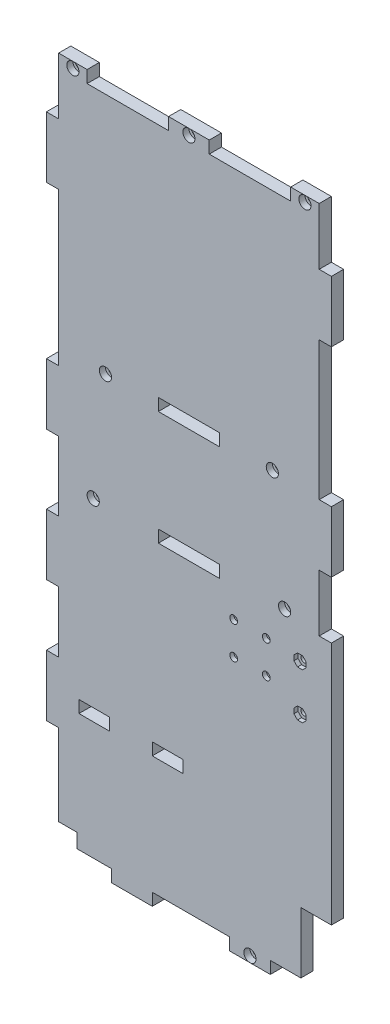
SolidWorks part; units mm, degrees
ref_plane "Plan de face" through (0, 0, 0) normal (0, 0, 1) x (1, 0, 0)
ref_plane "Plan de dessus" through (0, 0, 0) normal (0, 1, 0) x (1, 0, 0)
ref_plane "Plan de droite" through (0, 0, 0) normal (1, 0, 0) x (0, 0, -1)
sketch "Esquisse1" plane through (0, 0, 0) normal (0, 0, 1) x (1, 0, 0)
  line L0 (-67.6282, -207.2903) -> (-41.6282, -207.2903)
  line L1 (-67.6282, 126.7097) -> (-53.6282, 126.7097)
  line L2 (-67.6282, 126.7097) -> (-67.6282, 98.7097)
  line L3 (16.3718, -213.2903) -> (36.3718, -213.2903)
  line L4 (66.3718, 98.7097) -> (66.3718, 68.7097)
  line L5 (-67.6282, -100.2903) -> (-67.6282, -130.2903)
  line L6 (-67.6282, 98.7097) -> (-73.6282, 98.7097)
  line L7 (46.3718, 126.7097) -> (60.3718, 126.7097)
  line L8 (-67.6282, -70.2903) -> (-73.6282, -70.2903)
  line L9 (-67.6282, 68.7097) -> (-73.6282, 68.7097)
  line L10 (-73.6282, 98.7097) -> (-73.6282, 68.7097)
  line L11 (16.3718, -207.2903) -> (16.3718, -213.2903)
  line L12 (66.3718, -207.2903) -> (36.3718, -207.2903)
  line L13 (-67.6282, -6.2903) -> (-73.6282, -6.2903)
  line L14 (-67.6282, 68.7097) -> (-67.6282, -6.2903)
  line L15 (36.3718, -207.2903) -> (36.3718, -213.2903)
  line L16 (-67.6282, -36.2903) -> (-73.6282, -36.2903)
  line L17 (-73.6282, -6.2903) -> (-73.6282, -36.2903)
  line L18 (66.3718, 0.7097) -> (66.3718, -29.2903)
  line L19 (-53.6282, 126.7097) -> (-53.6282, 120.7097)
  line L20 (-53.6282, 120.7097) -> (-13.6282, 120.7097)
  line L21 (-13.6282, 120.7097) -> (-13.6282, 126.7097)
  line L22 (6.3718, 126.7097) -> (-13.6282, 126.7097)
  line L23 (66.3718, -57.2903) -> (66.3718, -207.2903)
  line L24 (66.3718, 68.7097) -> (60.3718, 68.7097)
  line L25 (6.3718, 126.7097) -> (6.3718, 120.7097)
  line L26 (66.3718, 0.7097) -> (60.3718, 0.7097)
  line L27 (66.3718, -57.2903) -> (60.3718, -57.2903)
  line L28 (6.3718, 120.7097) -> (46.3718, 120.7097)
  line L29 (66.3718, -29.2903) -> (60.3718, -29.2903)
  line L30 (60.3718, -57.2903) -> (60.3718, -29.2903)
  line L31 (60.3718, 68.7097) -> (60.3718, 0.7097)
  line L32 (46.3718, 120.7097) -> (46.3718, 126.7097)
  line L33 (60.3718, 126.7097) -> (60.3718, 98.7097)
  line L34 (60.3718, 98.7097) -> (66.3718, 98.7097)
  line L35 (-67.6282, -36.2903) -> (-67.6282, -70.2903)
  line L36 (-67.6282, -160.2903) -> (-67.6282, -207.2903)
  line L37 (-67.6282, -100.2903) -> (-73.6282, -100.2903)
  line L38 (-73.6282, -70.2903) -> (-73.6282, -100.2903)
  line L39 (-67.6282, -130.2903) -> (-73.6282, -130.2903)
  line L40 (-21.6282, -207.2903) -> (16.3718, -207.2903)
  line L41 (-67.6282, -160.2903) -> (-73.6282, -160.2903)
  line L42 (-73.6282, -130.2903) -> (-73.6282, -160.2903)
  line L44 (-21.6282, -207.2903) -> (-21.6282, -213.2903)
  line L45 (-21.6282, -213.2903) -> (-41.6282, -213.2903)
  line L46 (-41.6282, -207.2903) -> (-41.6282, -213.2903)
  point P0 (0, 0)
  dimension "D1" = 6
  dimension "D4" = 20
  dimension "D5" = 134
  dimension "D6" = 6
  dimension "D7" = 30
  dimension "D8" = 340
  dimension "D9" = 6
  dimension "D10" = 34
  dimension "D11" = 6
  dimension "D12" = 28
  dimension "D13" = 40
  dimension "D14" = 40
  dimension "D15" = 20
  dimension "D16" = 28
  dimension "D17" = 68
  dimension "D18" = 6
  dimension "D19" = 30
  dimension "D20" = 6
  dimension "D21" = 28
  dimension "D22" = 14
  dimension "D23" = 6
  dimension "D24" = 30
  dimension "D25" = 30
  dimension "D26" = 75
  dimension "D27" = 30
  dimension "D28" = 14
  dimension "D29" = 30
  dimension "D30" = 140
  dimension "D31" = 6
  dimension "D32" = 6
  dimension "D33" = 30
  dimension "D34" = 30
  dimension "D35" = 6
  dimension "D36" = 6
  dimension "D37" = 20
  dimension "D38" = 38
  dimension "D39" = 6
extrude "Boss.-Extru.1" add sketch "Esquisse1" along normal blind 6 contours L14 L13 L17 L16 L35 L8 L38 L37 L5 L39 L42 L41 L36 L0 L46 L45 L44 L40 L11 L3 L15 L12 L23 L27 L30 L29 L18 L26 L31 L24 L4 L34 L33 L7 L32 L28 L25 L22 L21 L20 L19 L1 L2 L6 L10 L9
sketch "Esquisse2" plane through (0, 0, 6) normal (0, 0, 1) x (1, 0, 0)
  line L0 (60.3718, 126.7097) -> (60.3718, 98.7097) construction
  line L1 (-18.6282, 4.7097) -> (11.3718, 4.7097)
  line L2 (-18.6282, 4.7097) -> (-18.6282, -1.2903)
  line L3 (-18.6282, -1.2903) -> (11.3718, -1.2903)
  line L4 (11.3718, 4.7097) -> (11.3718, -1.2903)
  line L5 (-18.6282, -57.2903) -> (11.3718, -57.2903)
  line L6 (-18.6282, -57.2903) -> (-18.6282, -51.2903)
  line L7 (-18.6282, -51.2903) -> (11.3718, -51.2903)
  line L8 (11.3718, -57.2903) -> (11.3718, -51.2903)
  line L9 (46.3718, 126.7097) -> (60.3718, 126.7097) construction
  line L11 (-67.6282, 126.7097) -> (-53.6282, 126.7097) construction
  line L13 (36.3718, -207.2903) -> (36.3718, -213.2903) construction
  line L16 (-73.6282, -6.2903) -> (-73.6282, -36.2903) construction
  line L17 (-67.6282, 126.7097) -> (-67.6282, 98.7097) construction
  line L18 (60.3718, 126.7097) -> (60.3718, 98.7097) construction
  line L19 (16.3718, -213.2903) -> (36.3718, -213.2903) construction
  line L21 (66.3718, 0.7097) -> (66.3718, -29.2903) construction
  line L22 (6.3718, 126.7097) -> (-13.6282, 126.7097) construction
  line L23 (6.3718, 126.7097) -> (6.3718, 120.7097) construction
  circle A0 centre (-44.6282, 1.7097) radius 1.5
  circle A1 centre (37.3718, 1.7097) radius 1.5
  circle A2 centre (43.3718, -54.2903) radius 1.5
  circle A3 centre (-50.6282, -54.2903) radius 1.5
  circle A4 centre (-3.6282, 123.7097) radius 1.5
  circle A5 centre (26.3718, -210.2903) radius 1.5
  circle A6 centre (-60.6282, 123.7097) radius 1.5
  circle A7 centre (53.3718, 123.7097) radius 1.5
  point P36 (36.3718, -210.2903)
  point P48 (26.3718, -213.2903)
  dimension "D2" = 3
  dimension "D5" = 3
  dimension "D8" = 3
  dimension "D9" = 10
  dimension "D14" = 3
  dimension "D19" = 3
  dimension "D24" = 3
  dimension "D28" = 3
  dimension "D35" = 3
  dimension "D7" = 7
  dimension "D10" = 7
  dimension "D4" = 3
  dimension "D11" = 3
  dimension "D12" = 10
  dimension "D1" = 7
  dimension "D3" = 3
  dimension "D6" = 3
  dimension "D13" = 26
  dimension "D15" = 6
  dimension "D16" = 30
  dimension "D17" = 55
  dimension "D18" = 26
  dimension "D20" = 3
  dimension "D21" = 3
  dimension "D22" = 50
  dimension "D23" = 156
  dimension "D27" = 32
  dimension "D29" = 6
  dimension "D30" = 3
  dimension "D31" = 32
  dimension "D32" = 3
  dimension "D33" = 55
  dimension "D34" = 30
extrude "Enlèv. mat.-Extru.1" cut sketch "Esquisse2" against normal through all
sketch "Esquisse3" plane through (0, 0, 6) normal (0, 0, 1) x (1, 0, 0)
  line L0 (-3.6282, 66.7097) -> (-3.6282, 77.4796) construction
  circle A0 centre (-3.6282, 123.7097) radius 2.995
  circle A1 centre (-60.6282, 123.7097) radius 2.995
  circle A2 centre (-44.6282, 1.7097) radius 3
  circle A3 centre (-50.6282, -54.2903) radius 3
  circle A4 centre (26.3718, -210.2903) radius 2.995
  circle A5 centre (43.3718, -54.2903) radius 3
  circle A6 centre (37.3718, 1.7097) radius 3
  circle A8 centre (53.3718, 123.7097) radius 2.995
  dimension "D1" = 6
  dimension "D2" = 6
  dimension "D3" = 5.99
  dimension "D4" = 5.99
  dimension "D5" = 5.99
extrude "Enlèv. mat.-Extru.2" cut sketch "Esquisse3" against normal blind 3
sketch "Esquisse4" plane through (0, 0, 6) normal (0, 0, 1) x (1, 0, 0)
  line L0 (26.3718, -213.2853) -> (26.3718, -171.7587) construction
  line L1 (66.3718, -207.2903) -> (36.3718, -207.2903) construction
  line L2 (66.3718, -57.2903) -> (66.3718, -207.2903) construction
  circle A0 centre (18.3618, -71.2903) radius 1.005
  circle A1 centre (34.3818, -71.2903) radius 1.005
  circle A2 centre (18.3668, -87.2903) radius 1.005
  circle A3 centre (34.3768, -87.2903) radius 1.005
  dimension "D1" = 2.01
  dimension "D2" = 2.01
  dimension "D3" = 2.01
  dimension "D4" = 2.01
  dimension "D12" = 120
  dimension "D14" = 31.995
  dimension "D5" = 8.005
  dimension "D6" = 8.005
  dimension "D7" = 16
  dimension "D8" = 16.01
  dimension "D9" = 16
  dimension "D10" = 8.01
  dimension "D11" = 8.01
  dimension "D13" = 40
extrude "Enlèv. mat.-Extru.4" cut sketch "Esquisse4" against normal through all
sketch "Esquisse5" plane through (0, 0, 6) normal (0, 0, 1) x (1, 0, 0)
  circle A0 centre (18.3618, -71.2903) radius 1.9
  circle A1 centre (34.3818, -71.2903) radius 1.9
  circle A2 centre (34.3768, -87.2903) radius 1.9
  circle A3 centre (18.3668, -87.2903) radius 1.9
  dimension "D1" = 3.8
  dimension "D2" = 3.8
  dimension "D3" = 3.8
  dimension "D4" = 3.8
extrude "Enlèv. mat.-Extru.5" cut sketch "Esquisse5" against normal blind 2
sketch "Esquisse6" plane through (0, 0, 6) normal (0, 0, 1) x (1, 0, 0)
  line L0 (-67.6282, -160.2903) -> (-67.6282, -207.2903) construction
  line L1 (51.3718, -177.2903) -> (66.3718, -177.2903)
  line L2 (51.3718, -177.2903) -> (51.3718, -207.2903)
  line L3 (51.3718, -207.2903) -> (66.3718, -207.2903)
  line L4 (66.3718, -177.2903) -> (66.3718, -207.2903)
  line L5 (-67.6282, -207.2903) -> (-58.6282, -207.2903)
  line L6 (-67.6282, -207.2903) -> (-67.6282, -200.2903)
  line L7 (-67.6282, -200.2903) -> (-58.6282, -200.2903)
  line L8 (-58.6282, -207.2903) -> (-58.6282, -200.2903)
  line L10 (-67.6282, -207.2903) -> (-41.6282, -207.2903) construction
  dimension "D1" = 15
  dimension "D2" = 30
  dimension "D3" = 9
  dimension "D4" = 7
  dimension "D5" = 0
  dimension "D6" = 0
extrude "Enlèv. mat.-Extru.6" cut sketch "Esquisse6" against normal through all
sketch "Esquisse7" plane through (0, 0, 6) normal (0, 0, 1) x (1, 0, 0)
  line L0 (66.3718, -57.2903) -> (66.3718, -177.2903) construction
  circle A0 centre (50.9718, -72.7903) radius 1.6
  circle A1 centre (50.9718, -95.3424) radius 1.6
  dimension "D2" = 3.2
  dimension "D3" = 15.4
  dimension "D1" = 3.2
  dimension "D4" = 15.4
  dimension "D5" = 22.552
extrude "Enlèv. mat.-Extru.7" cut sketch "Esquisse7" against normal through all
sketch "Esquisse8" plane through (0, 0, 6) normal (0, 0, 1) x (1, 0, 0)
  line L0 (83.9823, -52.1389) -> (651.3157, -52.1389) construction
  line L1 (1.3499, 70.3968) -> (-1.1808, 73.8464) construction
  line L2 (-1.1808, 73.8464) -> (-7.7897, 74.7329) construction
  line L3 (-7.7897, 74.7329) -> (-13.8864, 72.5785) construction
  line L4 (-13.8864, 72.5785) -> (-14.9894, 68.8696) construction
  line L5 (-14.9894, 68.8696) -> (-14.9091, 62.6769) construction
  line L6 (-14.9091, 62.6769) -> (-4.4466, 64.8566) construction
  line L7 (-4.4466, 64.8566) -> (4.3644, 70.1002) construction
  line L8 (51.1643, 70.3337) -> (48.637, 73.7776) construction
  line L9 (48.637, 73.7776) -> (42.0281, 74.6642) construction
  line L10 (42.0281, 74.6642) -> (35.9314, 72.5097) construction
  line L11 (35.9314, 72.5097) -> (34.8284, 68.8008) construction
  line L12 (34.8284, 68.8008) -> (34.9087, 62.6081) construction
  line L13 (34.9087, 62.6081) -> (45.3712, 64.7878) construction
  line L14 (45.3712, 64.7878) -> (54.1822, 70.0314) construction
  line L15 (-59.6265, 73.8848) -> (-41.2741, 73.8848)
  line L16 (-41.2741, 72.3748) -> (-53.9387, 72.3748)
  line L17 (-53.9387, 72.3748) -> (-53.9387, 66.1551)
  line L18 (-53.9387, 66.1551) -> (-42.0323, 66.1551)
  line L19 (-42.0323, 64.6451) -> (-53.9384, 64.6451)
  line L20 (-53.9384, 64.6451) -> (-53.9384, 57.7567)
  line L21 (-53.9384, 57.7567) -> (-41.12, 57.7567)
  line L22 (-41.1203, 56.2467) -> (-59.6265, 56.2467)
  line L23 (-59.6265, 56.2467) -> (-59.6265, 73.8848)
  line L24 (-35.7911, 73.8848) -> (-30.1988, 73.8848)
  line L25 (-30.1988, 73.8848) -> (-30.1988, 57.7567)
  line L26 (-30.1988, 57.7567) -> (-17.7337, 57.7567)
  line L27 (-17.7337, 57.7567) -> (-17.7337, 56.2467)
  line L28 (-17.7337, 56.2467) -> (-35.7911, 56.2467)
  line L29 (-35.7911, 56.2467) -> (-35.7911, 73.8848)
  line L30 (16.4667, 56.2683) -> (22.2354, 56.2683)
  line L31 (22.2354, 56.2683) -> (22.2354, 65.055)
  line L32 (-59.6265, 53.0005) -> (53.9068, 53.0005)
  line L33 (53.9068, 51.4905) -> (-59.6265, 51.4905)
  line L34 (-43.772, 49.309) -> (-36.2629, 49.309)
  line L35 (-43.772, 49.309) -> (-43.772, 41.5946)
  line L36 (-43.772, 41.5946) -> (-37.2502, 41.5946)
  line L37 (-42.3907, 48.703) -> (-42.3907, 42.328)
  line L38 (-42.3907, 42.328) -> (-37.2502, 42.328)
  line L39 (-42.3907, 48.703) -> (-37.2502, 48.703)
  line L40 (-36.2629, 49.309) -> (-32.9438, 48.5026) construction
  line L41 (-32.9438, 48.5026) -> (-32.4277, 47.6316) construction
  line L42 (-32.4277, 47.6316) -> (-31.2664, 45.2123) construction
  line L43 (-31.2664, 45.2123) -> (-33.1697, 42.3414) construction
  line L44 (-33.1697, 42.3414) -> (-33.7342, 42.3414) construction
  line L45 (-33.7342, 42.3414) -> (-35.718, 41.8414) construction
  line L46 (-35.718, 41.8414) -> (-37.2502, 41.5946) construction
  line L47 (-37.2502, 48.703) -> (-34.8471, 48.1478) construction
  line L48 (-34.8471, 48.1478) -> (-32.8793, 47.8574) construction
  line L49 (-32.8793, 47.8574) -> (-33.1051, 44.3091) construction
  line L50 (-33.1051, 44.3091) -> (-33.6896, 44.5196) construction
  line L51 (-33.6896, 44.5196) -> (-34.3632, 42.9543) construction
  line L52 (-34.3632, 42.9543) -> (-35.4449, 43.005) construction
  line L53 (-35.4449, 43.005) -> (-36.4604, 42.328) construction
  line L54 (-36.4604, 42.328) -> (-37.2502, 42.328) construction
  line L55 (-22.9696, 49.3203) -> (-22.9696, 41.6299)
  line L56 (-22.9696, 41.6299) -> (-15.266, 41.6299)
  line L57 (-15.266, 41.6299) -> (-15.266, 42.2703)
  line L58 (-41.2741, 73.8848) -> (-41.2741, 72.3748)
  line L59 (-42.0323, 66.1551) -> (-42.0323, 64.6451)
  line L60 (-41.12, 57.7567) -> (-41.1203, 56.2467)
  line L61 (4.3644, 70.1002) -> (9.86, 66.5211) construction
  line L62 (9.86, 66.5211) -> (10.9285, 63.9955) construction
  line L63 (10.9285, 63.9955) -> (7.8116, 56.2683) construction
  line L64 (7.8116, 56.2683) -> (2.5385, 53.3236) construction
  line L65 (2.5385, 53.3236) -> (-2.5931, 56.2692) construction
  line L66 (-2.5931, 56.2692) -> (-5.2193, 54.6946) construction
  line L67 (-5.2193, 54.6946) -> (-8.3815, 55.87) construction
  line L68 (-8.3815, 55.87) -> (-12.7706, 55.6734) construction
  line L69 (-12.7706, 55.6734) -> (-13.8206, 57.4169) construction
  line L70 (-13.8206, 57.4169) -> (-15.3675, 58.365) construction
  line L71 (1.3499, 70.3968) -> (3.2735, 71.2107)
  line L72 (-15.3675, 58.365) -> (-13.3684, 59.2107)
  line L73 (3.2735, 71.2107) -> (0.4559, 73.6574) construction
  line L74 (0.4559, 73.6574) -> (-2.6096, 74.038) construction
  line L75 (-2.6096, 74.038) -> (-4.829, 74.8358) construction
  line L76 (-4.829, 74.8358) -> (-8.7037, 74.038) construction
  line L77 (-8.7037, 74.038) -> (-9.8639, 74.5144) construction
  line L78 (-9.8639, 74.5144) -> (-13.292, 75.8714) construction
  line L79 (-13.292, 75.8714) -> (-15.2871, 71.2982) construction
  line L80 (-15.2871, 71.2982) -> (-19.9947, 71.9522) construction
  line L81 (-19.9947, 71.9522) -> (-22.0559, 66.9924) construction
  line L82 (-22.0559, 66.9924) -> (-17.3626, 63.9556) construction
  line L83 (-17.3626, 63.9556) -> (-13.5729, 63.9054) construction
  line L84 (-13.5729, 63.9054) -> (-10.615, 64.6085) construction
  line L85 (-10.615, 64.6085) -> (-8.478, 64.5579) construction
  line L86 (-8.478, 64.5579) -> (-6.7924, 63.7325) construction
  line L87 (-6.7924, 63.7325) -> (-5.1149, 64.0058) construction
  line L88 (-5.1149, 64.0058) -> (0.2138, 63.9409) construction
  line L89 (0.2138, 63.9409) -> (0.5272, 62.7654) construction
  line L90 (0.5272, 62.7654) -> (3.5576, 59.735) construction
  line L91 (3.5576, 59.735) -> (-1.0924, 58.4549) construction
  line L92 (-1.0924, 58.4549) -> (-2.477, 55.0849) construction
  line L93 (-2.477, 55.0849) -> (-5.8959, 57.6075) construction
  line L94 (-5.8959, 57.6075) -> (-8.6162, 56.2082) construction
  line L95 (-8.6162, 56.2082) -> (-11.0371, 57.4449) construction
  line L96 (-11.0371, 57.4449) -> (-13.3684, 59.2107) construction
  line L97 (52.8368, 71.2065) -> (50.0192, 73.6533) construction
  line L98 (50.0192, 73.6533) -> (46.9537, 74.0339) construction
  line L99 (46.9537, 74.0339) -> (44.7343, 74.8317) construction
  line L100 (44.7343, 74.8317) -> (40.8596, 74.0339) construction
  line L101 (40.8596, 74.0339) -> (39.6994, 74.5103) construction
  line L102 (39.6994, 74.5103) -> (36.2713, 75.8672) construction
  line L103 (36.2713, 75.8672) -> (34.2762, 71.294) construction
  line L104 (34.2762, 71.294) -> (29.5686, 71.9481) construction
  line L105 (29.5686, 71.9481) -> (27.5074, 66.9882) construction
  line L106 (27.5074, 66.9882) -> (32.2007, 63.9514) construction
  line L107 (32.2007, 63.9514) -> (35.9904, 63.9012) construction
  line L108 (35.9904, 63.9012) -> (38.9483, 64.6044) construction
  line L109 (38.9483, 64.6044) -> (41.0853, 64.5538) construction
  line L110 (41.0853, 64.5538) -> (42.7709, 63.7283) construction
  line L111 (42.7709, 63.7283) -> (44.4484, 64.0016) construction
  line L112 (44.4484, 64.0016) -> (49.7771, 63.9368) construction
  line L113 (49.7771, 63.9368) -> (50.0906, 62.7612) construction
  line L114 (50.0906, 62.7612) -> (53.1209, 59.7308) construction
  line L115 (53.1209, 59.7308) -> (48.4709, 58.4507) construction
  line L116 (48.4709, 58.4507) -> (47.0863, 55.0807) construction
  line L117 (47.0863, 55.0807) -> (43.6674, 57.6033) construction
  line L118 (43.6674, 57.6033) -> (40.9471, 56.2041) construction
  line L119 (40.9471, 56.2041) -> (38.5262, 57.4408) construction
  line L120 (38.5262, 57.4408) -> (36.1068, 59.361) construction
  line L121 (54.1822, 70.0314) -> (59.6779, 66.4523) construction
  line L122 (59.6779, 66.4523) -> (60.7464, 63.9267) construction
  line L123 (60.7464, 63.9267) -> (57.6294, 56.1995) construction
  line L124 (57.6294, 56.1995) -> (52.3563, 53.2548) construction
  line L125 (52.3563, 53.2548) -> (47.2247, 56.2004) construction
  line L126 (47.2247, 56.2004) -> (44.5985, 54.6258) construction
  line L127 (44.5985, 54.6258) -> (41.4363, 55.8012) construction
  line L128 (41.4363, 55.8012) -> (37.0472, 55.6047) construction
  line L129 (37.0472, 55.6047) -> (35.9972, 57.3481) construction
  line L130 (35.9972, 57.3481) -> (34.3622, 58.4506) construction
  line L131 (52.8368, 71.2065) -> (51.1643, 70.3337)
  line L132 (36.1068, 59.361) -> (34.3622, 58.4506)
  line L133 (22.2354, 65.055) -> (32.2776, 73.6627)
  line L134 (32.2776, 73.6627) -> (28.8737, 73.6627)
  line L135 (28.8737, 73.6627) -> (20.7947, 66.7379)
  line L136 (20.7947, 66.7379) -> (12.5473, 73.6627)
  line L137 (12.5473, 73.6627) -> (5.8208, 73.6627)
  line L138 (5.8208, 73.6627) -> (16.4667, 64.724)
  line L139 (16.4667, 64.724) -> (16.4667, 56.2683)
  line L140 (-59.6265, 53.0005) -> (-59.6265, 51.4905)
  line L141 (53.9068, 53.0005) -> (53.9068, 51.4905)
  line L142 (-15.266, 42.2703) -> (-21.7665, 42.2703)
  line L143 (-21.7665, 42.2703) -> (-21.7665, 45.2123)
  line L144 (-21.7665, 45.2123) -> (-15.5948, 45.2123)
  line L145 (-15.5948, 45.2123) -> (-15.5948, 45.8869)
  line L146 (-15.5948, 45.8869) -> (-21.7665, 45.8869)
  line L147 (-21.7665, 45.8869) -> (-21.7665, 48.6618)
  line L148 (-21.7665, 48.6618) -> (-15.266, 48.6618)
  line L149 (-15.266, 48.6618) -> (-15.266, 49.3203)
  line L150 (-15.266, 49.3203) -> (-22.9696, 49.3203)
  line L151 (1.4818, 48.1478) -> (1.4818, 49.0566) construction
  line L152 (11.347, 49.3203) -> (13.07, 49.3203)
  line L153 (11.347, 49.3203) -> (11.347, 41.6299)
  line L154 (11.347, 41.6299) -> (13.07, 41.6299)
  line L155 (13.07, 49.3203) -> (13.07, 41.6299)
  line L156 (1.4818, 49.0566) -> (-1.3581, 48.6978) construction
  line L157 (-1.3581, 48.6978) -> (-2.823, 49.3203) construction
  line L158 (-2.823, 49.3203) -> (-4.8259, 49.0865) construction
  line L159 (-4.8259, 49.0865) -> (-8.1143, 48.1896) construction
  line L160 (-8.1143, 48.1896) -> (-7.2174, 46.1568) construction
  line L161 (-7.2174, 46.1568) -> (-5.9983, 45.4234) construction
  line L162 (-5.9983, 45.4234) -> (-3.4494, 44.2831) construction
  line L163 (-3.4494, 44.2831) -> (5.1627, 48.2962) construction
  line L164 (5.1627, 48.2962) -> (7.102, 46.5454) construction
  line L165 (7.102, 46.5454) -> (5.129, 40.3872) construction
  line L166 (5.129, 40.3872) -> (-0.551, 39.9687) construction
  line L167 (-0.551, 39.9687) -> (-3.2116, 41.284) construction
  line L168 (-3.2116, 41.284) -> (-5.4238, 41.6129) construction
  line L169 (-5.4238, 41.6129) -> (-6.1711, 41.8414) construction
  line L170 (1.4818, 48.1478) -> (1.4818, 49.0566)
  line L171 (-6.1711, 41.8414) -> (-6.1711, 42.9543)
  line L172 (1.4818, 49.0566) -> (0.017, 49.4153) construction
  line L173 (0.017, 49.4153) -> (-1.9859, 49.4153) construction
  line L174 (-1.9859, 49.4153) -> (-3.9888, 49.4153) construction
  line L175 (-3.9888, 49.4153) -> (-9.6987, 50.2822) construction
  line L176 (-9.6987, 50.2822) -> (-6.6793, 47.0536) construction
  line L177 (-6.6793, 47.0536) -> (-10.745, 45.0507) construction
  line L178 (-10.745, 45.0507) -> (-4.7238, 44.8532) construction
  line L179 (-4.7238, 44.8532) -> (-2.5539, 45.4393) construction
  line L180 (-2.5539, 45.4393) -> (0.2493, 45.3351) construction
  line L181 (0.2493, 45.3351) -> (2.0199, 46.5454) construction
  line L182 (2.0199, 46.5454) -> (3.425, 42.5396) construction
  line L183 (3.425, 42.5396) -> (1.4221, 41.4335) construction
  line L184 (1.4221, 41.4335) -> (-1.6272, 41.7025) construction
  line L185 (-1.6272, 41.7025) -> (-4.0046, 42.0521) construction
  line L186 (-4.0046, 42.0521) -> (-6.1711, 42.9543) construction
  line L187 (32.2325, 48.2962) -> (28.8027, 48.8654) construction
  line L188 (28.8027, 48.8654) -> (23.8147, 49.1444) construction
  line L189 (23.8147, 49.1444) -> (22.7334, 46.7027) construction
  line L190 (22.7334, 46.7027) -> (22.8032, 43.8076) construction
  line L191 (22.8032, 43.8076) -> (25.21, 42.4822) construction
  line L192 (25.21, 42.4822) -> (27.6167, 42.1334) construction
  line L193 (32.2325, 45.3351) -> (32.2325, 42.1334)
  line L194 (27.6167, 42.1334) -> (29.7359, 41.8203) construction
  line L195 (32.2325, 45.3351) -> (33.6064, 45.3351)
  line L196 (33.6064, 45.3351) -> (33.6064, 41.6299)
  line L197 (33.6064, 41.6299) -> (32.1861, 41.4009) construction
  line L198 (32.1861, 41.4009) -> (30.163, 41.4009) construction
  line L199 (30.163, 41.4009) -> (27.7563, 41.4009) construction
  line L200 (27.7563, 41.4009) -> (25.21, 41.1916) construction
  line L201 (25.21, 41.1916) -> (22.9078, 41.8194) construction
  line L202 (22.9078, 41.8194) -> (21.3382, 43.2147) construction
  line L203 (21.3382, 43.2147) -> (21.0591, 46.04) construction
  line L204 (21.0591, 46.04) -> (22.0358, 48.4119) construction
  line L205 (22.0358, 48.4119) -> (25.1516, 49.0696) construction
  line L206 (25.1516, 49.0696) -> (27.0238, 49.4583) construction
  line L207 (27.0238, 49.4583) -> (31.0883, 49.4583)
  line L208 (31.0883, 49.4583) -> (32.6027, 49.1887) construction
  line L209 (32.6027, 49.1887) -> (32.9543, 48.8507) construction
  line L210 (32.2325, 48.2962) -> (32.9543, 48.2962)
  line L211 (32.9543, 48.2962) -> (32.9543, 48.8507)
  line L212 (29.7359, 41.8203) -> (32.2325, 42.1334) construction
  line L213 (43.6426, 41.6299) -> (43.6426, 49.1887)
  line L214 (43.6426, 49.1887) -> (45.582, 49.1887)
  line L215 (45.582, 49.1887) -> (52.4179, 42.3528)
  line L216 (52.4179, 42.3528) -> (52.7706, 42.3528)
  line L217 (52.7706, 42.3528) -> (52.7706, 49.1887)
  line L218 (52.7706, 49.1887) -> (53.8711, 49.1887)
  line L219 (53.8711, 49.1887) -> (53.8711, 41.6331)
  line L220 (53.8711, 41.6331) -> (52.0126, 41.6331)
  line L221 (52.0126, 41.6331) -> (45.1883, 48.4574)
  line L222 (45.1883, 48.4574) -> (44.7514, 48.4574)
  line L223 (44.7514, 48.4574) -> (44.7514, 41.6299)
  line L224 (44.7514, 41.6299) -> (43.6426, 41.6299)
  spline_without_curve S0
  spline_without_curve S1
  spline_without_curve S2
  spline_without_curve S3
  spline_without_curve S4
  spline_without_curve S5
  spline_without_curve S6
  spline_without_curve S7
  spline_without_curve S8
  spline_without_curve S9
  spline S10 degree 2 poles (31.0883, 49.4583) (32.6027, 49.1887) (32.9543, 48.8507) knots 0 0 0 1 1 1
  spline S11 degree 2 poles (27.6167, 42.1334) (29.7359, 41.8203) (32.2325, 42.1334) knots 0 0 0 1 1 1
  dimension "D1" = 1.51
  dimension "D2" = 1.51
  dimension "D3" = 1.51
  dimension "D4" = 1.51
  dimension "D6" = 1.51
sketch "Esquisse10" plane through (0, 0, 6) normal (0, 0, 1) x (1, 0, 0)
  line L0 (-67.6282, -36.2903) -> (-67.6282, -70.2903) construction
  line L1 (-57.6282, -143.2903) -> (-42.6282, -143.2903)
  line L2 (-57.6282, -143.2903) -> (-57.6282, -149.2903)
  line L3 (-57.6282, -149.2903) -> (-42.6282, -149.2903)
  line L4 (-42.6282, -143.2903) -> (-42.6282, -149.2903)
  line L5 (-21.6282, -143.2903) -> (-6.6282, -143.2903)
  line L6 (-21.6282, -143.2903) -> (-21.6282, -149.2903)
  line L7 (-21.6282, -149.2903) -> (-6.6282, -149.2903)
  line L8 (-6.6282, -143.2903) -> (-6.6282, -149.2903)
  line L9 (-58.6282, -207.2903) -> (-41.6282, -207.2903) construction
  line L10 (-42.6282, -143.2903) -> (-21.6282, -143.2903) construction
  line L11 (-42.6282, -149.2903) -> (-21.6282, -149.2903) construction
  dimension "D1" = 15
  dimension "D2" = 15
  dimension "D3" = 21
  dimension "D4" = 10
  dimension "D5" = 6
  dimension "D7" = 58
extrude "Enlèv. mat.-Extru.9" cut sketch "Esquisse10" against normal through all
sketch "Esquisse11" plane through (0, 0, 6) normal (0, 0, 1) x (1, 0, 0)
  line L0 (49.7291, -69.7903) -> (52.2144, -69.7903)
  line L1 (52.2144, -69.7903) -> (53.9718, -71.5477)
  line L2 (53.9718, -71.5477) -> (53.9718, -74.033)
  line L3 (53.9718, -74.033) -> (52.2144, -75.7903)
  line L4 (52.2144, -75.7903) -> (49.7291, -75.7903)
  line L5 (49.7291, -75.7903) -> (47.9718, -74.033)
  line L6 (47.9718, -74.033) -> (47.9718, -71.5477)
  line L7 (47.9718, -71.5477) -> (49.7291, -69.7903)
  line L8 (49.7291, -69.7903) -> (49.7291, -75.7903) construction
  line L9 (52.2144, -75.7903) -> (52.2144, -69.7903) construction
  line L10 (47.9718, -71.5477) -> (53.9718, -71.5477) construction
  line L11 (53.9718, -74.033) -> (47.9718, -74.033) construction
  line L12 (53.0931, -74.9117) -> (48.8504, -70.669) construction
  line L13 (53.0931, -70.669) -> (48.8504, -74.9117) construction
  line L14 (50.9718, -95.3424) -> (50.9718, -72.7903) construction
  line L15 (50.9718, -84.0664) -> (66.3718, -84.0664) construction
  line L16 (66.3718, -57.2903) -> (66.3718, -177.2903) construction
  line L17 (53.0931, -97.4637) -> (48.8504, -93.2211) construction
  line L18 (53.0931, -93.2211) -> (48.8504, -97.4637) construction
  line L19 (53.9718, -94.0997) -> (47.9718, -94.0997) construction
  line L20 (47.9718, -96.585) -> (53.9718, -96.585) construction
  line L21 (52.2144, -92.3424) -> (52.2144, -98.3424) construction
  line L22 (49.7291, -98.3424) -> (49.7291, -92.3424) construction
  line L23 (47.9718, -96.585) -> (49.7291, -98.3424)
  line L24 (47.9718, -94.0997) -> (47.9718, -96.585)
  line L25 (49.7291, -92.3424) -> (47.9718, -94.0997)
  line L26 (52.2144, -92.3424) -> (49.7291, -92.3424)
  line L27 (53.9718, -94.0997) -> (52.2144, -92.3424)
  line L28 (53.9718, -96.585) -> (53.9718, -94.0997)
  line L29 (52.2144, -98.3424) -> (53.9718, -96.585)
  line L30 (49.7291, -98.3424) -> (52.2144, -98.3424)
  circle A1 centre (50.9718, -72.7903) radius 1.6
  circle A2 centre (50.9718, -95.3424) radius 1.6
  dimension "D1" = 6
extrude "Enlèv. mat.-Extru.10" cut sketch "Esquisse11" against normal blind 2
